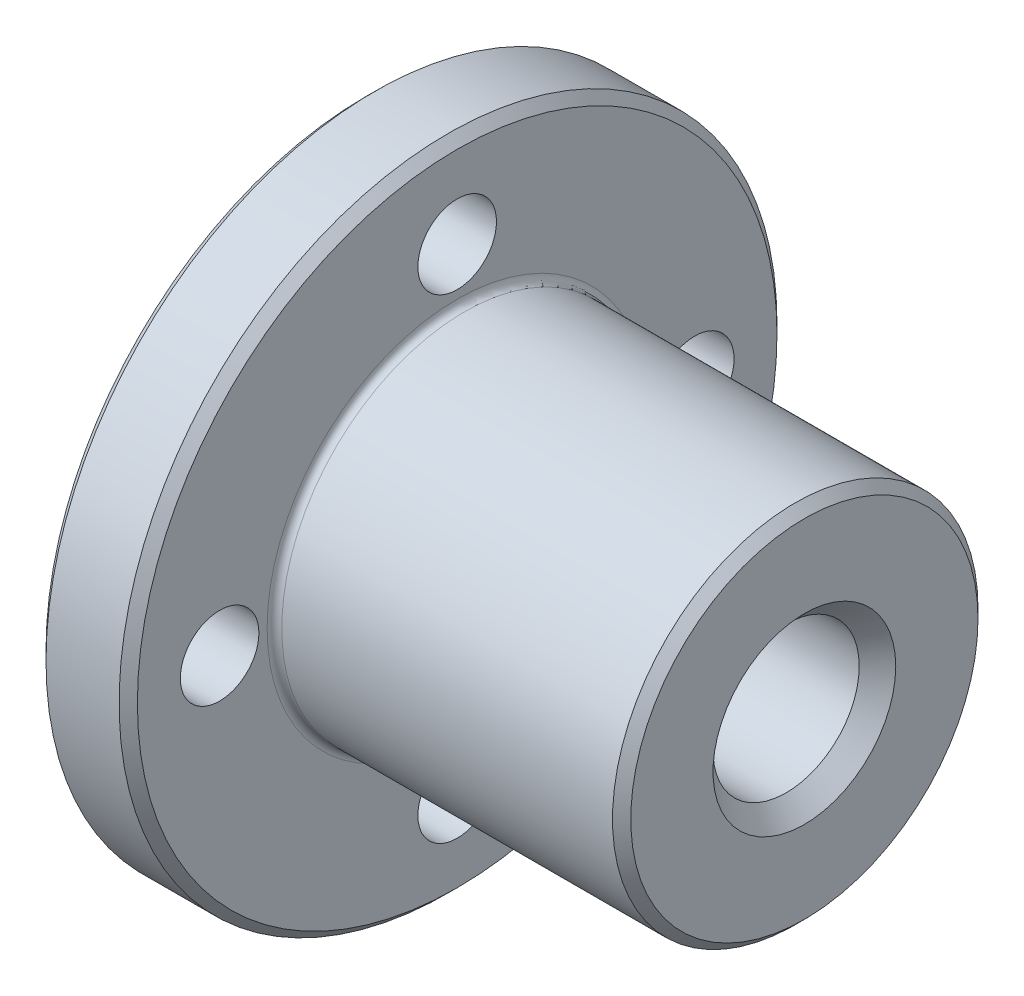
SolidWorks part; units mm, degrees
material "Brass"
ref_plane "Front Plane" through (0, 0, 0) normal (0, 0, 1) x (1, 0, 0)
ref_plane "Top Plane" through (0, 0, 0) normal (0, 1, 0) x (1, 0, 0)
ref_plane "Right Plane" through (0, 0, 0) normal (1, 0, 0) x (0, 0, -1)
sketch "Sketch1" plane through (0, 0, 0) normal (0, 0, 1) x (1, 0, 0)
  line L0 (0, 18) -> (0, 0)
  line L1 (0, 0) -> (5, 0)
  line L2 (5, 0) -> (5, 18)
  line L3 (5, 18) -> (0, 18)
  line L4 (0, 0) -> (5, 0) construction
revolve "Revolve1" add sketch "Sketch1" angle 360 about L4
sketch "Sketch2" plane through (5, 0, 0) normal (1, 0, 0) x (0, 0, -1)
  circle A0 centre (0, 0) radius 10
extrude "Boss-Extrude1" add sketch "Sketch2" along normal blind 19
hole_wizard "Ø4.3 (4.3) Diameter Hole1" positions "Sketch4" profile "Sketch3" hole size "Ø4.3" standard "ANSI Metric"
sketch "Sketch4" plane through (0, 0, 0) normal (-1, 0, 0) x (0, 0, 1)
  point P0 (0, 13)
  point P1 (0, -13)
  point P2 (-13, 0)
  point P3 (13, 0)
sketch "Sketch3" plane through (0, 13, 0) normal (0, 1, 0) x (0, 0, 1)
  line L0 (0, 0) -> (0, 24)
  line L1 (0, 24) -> (2.15, 24)
  line L2 (2.15, 24) -> (2.15, 0)
  line L5 (2.15, 0) -> (0, 0)
  line L11 (0, -6.35) -> (0, 107.95) construction
  dimension "Thru Hole Dia." = 4.3
  dimension "Thru Hole Depth" = 24
hole_wizard "Ø8.0 (8) Diameter Hole1" positions "Sketch6" profile "Sketch5" hole size "Ø8.0" standard "ANSI Metric"
sketch "Sketch6" plane through (24, 0, 0) normal (1, 0, 0) x (0, 0, -1)
  point P0 (0, 0)
sketch "Sketch5" plane through (24, 0, 0) normal (0, 1, 0) x (0, 0, -1)
  line L0 (0, 0) -> (0, 24)
  line L1 (0, 24) -> (4, 24)
  line L2 (4, 24) -> (4, 0)
  line L5 (4, 0) -> (0, 0)
  line L11 (0, -6.35) -> (0, 107.95) construction
  dimension "Thru Hole Dia." = 8
  dimension "Thru Hole Depth" = 24
chamfer "Chamfer1" distance 0.5 angle 45 3 edges at (5, 0, -18) (0, 0, -18) (24, 0, -10)
chamfer "Chamfer2" distance 1 angle 45 2 edges at (0, 0, -4) (24, 0, -4)
fillet "Fillet1" radius 0.4 1 edges at (5, 0, -10)
